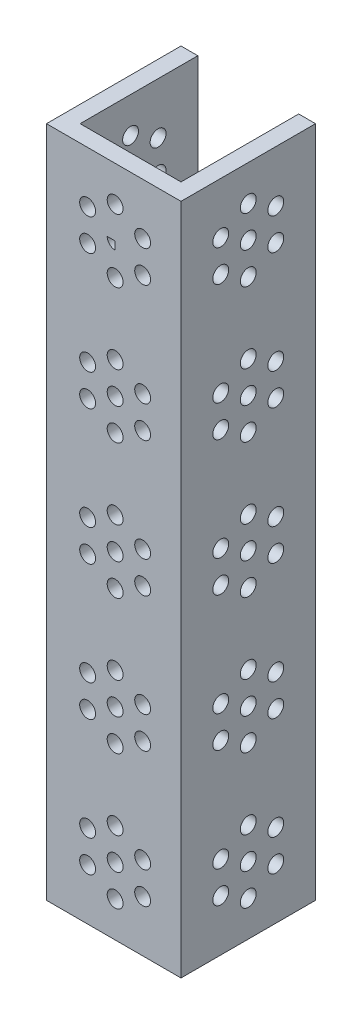
SolidWorks part; units mm, degrees
ref_plane "Front" through (0, 0, 0) normal (0, 0, 1) x (1, 0, 0)
ref_plane "Top" through (0, 0, 0) normal (0, 1, 0) x (1, 0, 0)
ref_plane "Right" through (0, 0, 0) normal (1, 0, 0) x (0, 0, -1)
sketch "Sketch2" plane through (0, 0, 0) normal (0, 1, 0) x (1, 0, 0)
  line L0 (12.7, 25.4) -> (12.7, 3.175)
  line L1 (0, 0) -> (25.4, 0)
  line L2 (0, 0) -> (0, 25.4)
  line L3 (0, 25.4) -> (25.4, 25.4)
  line L4 (25.4, 0) -> (25.4, 25.4)
  line L5 (12.7, 3.175) -> (22.225, 3.175)
  line L6 (12.7, 3.175) -> (3.175, 3.175)
  line L7 (3.175, 3.175) -> (3.175, 25.4)
  line L8 (22.225, 3.175) -> (22.225, 25.4)
  dimension "D1" = 25.4
  dimension "D2" = 25.4
  dimension "D3" = 22.225
  dimension "D4" = 9.525
  dimension "D5" = 9.525
extrude "Boss-Extrude1" add sketch "Sketch2" along normal blind 127 contours L8 L5 L6 L7 L3 L2 L1 L4
sketch "Sketch3" plane through (0, 0, 0) normal (-1, 0, 0) x (0, 0, 1)
  line L0 (-25.4, 0) -> (-25.4, 25.4)
  line L1 (-25.4, 127) -> (-25.4, 0) construction
  circle A0 centre (-12.7, 12.7) radius 1.5
  circle A1 centre (-12.7, 18.7) radius 1.5
  circle A2 centre (-7.5038, 15.7) radius 1.5
  circle A3 centre (-7.5038, 9.7) radius 1.5
  circle A4 centre (-12.7, 6.7) radius 1.5
  circle A5 centre (-17.8962, 9.7) radius 1.5
  circle A6 centre (-17.8962, 15.7) radius 1.5
  circle A7 centre (-12.7, 32.1) radius 1.5
  circle A8 centre (-17.8962, 35.1) radius 1.5
  circle A9 centre (-17.8962, 41.1) radius 1.5
  circle A10 centre (-12.7, 38.1) radius 1.5
  circle A11 centre (-12.7, 44.1) radius 1.5
  circle A12 centre (-7.5038, 41.1) radius 1.5
  circle A13 centre (-7.5038, 35.1) radius 1.5
  circle A14 centre (-12.7, 57.5) radius 1.5
  circle A15 centre (-17.8962, 60.5) radius 1.5
  circle A16 centre (-17.8962, 66.5) radius 1.5
  circle A17 centre (-12.7, 63.5) radius 1.5
  circle A18 centre (-12.7, 69.5) radius 1.5
  circle A19 centre (-7.5038, 66.5) radius 1.5
  circle A20 centre (-7.5038, 60.5) radius 1.5
  circle A21 centre (-12.7, 82.9) radius 1.5
  circle A22 centre (-17.8962, 85.9) radius 1.5
  circle A23 centre (-17.8962, 91.9) radius 1.5
  circle A24 centre (-12.7, 88.9) radius 1.5
  circle A25 centre (-12.7, 94.9) radius 1.5
  circle A26 centre (-7.5038, 91.9) radius 1.5
  circle A27 centre (-7.5038, 85.9) radius 1.5
  circle A28 centre (-12.7, 108.3) radius 1.5
  circle A29 centre (-17.8962, 111.3) radius 1.5
  circle A30 centre (-17.8962, 117.3) radius 1.5
  circle A31 centre (-12.7, 114.3) radius 1.5
  circle A32 centre (-12.7, 120.3) radius 1.5
  circle A33 centre (-7.5038, 117.3) radius 1.5
  circle A34 centre (-7.5038, 111.3) radius 1.5
  point P26 (-12.7, 12.7)
  dimension "D3" = 6
  dimension "D1" = 25.4
  dimension "D2" = 6
  dimension "D4" = 5
extrude "Cut-Extrude1" cut sketch "Sketch3" against normal through all contours A5 | A6 | A1 | A0 | A4 | A3 | A2 | A8 | A9 | A11 | A10 | A13 | A12 | A14 | A17 | A7 | A15 | A16 | A18 | A19 | A20 | A22 | A23 | A21 | A24 | A27 | A26 | A25 | A29 | A28 | A30 | A32 | A31 | A34 | A33
sketch "Sketch4" plane through (0, 0, 0) normal (0, 0, 1) x (1, 0, 0)
  line L0 (0, 127) -> (0, 101.6)
  line L1 (0, 127) -> (0, 0) construction
  line L2 (0, 114.3) -> (25.4, 114.3)
  line L3 (25.4, 127) -> (25.4, 0) construction
  line L4 (12.9637, 114.3) -> (12.9637, 108.3)
  circle A0 centre (12.9637, 114.3) radius 1.5
  circle A1 centre (12.9637, 108.3) radius 1.5
  circle A2 centre (7.7675, 111.3) radius 1.5
  circle A3 centre (7.7675, 117.3) radius 1.5
  circle A4 centre (12.9637, 120.3) radius 1.5
  circle A5 centre (18.1598, 117.3) radius 1.5
  circle A6 centre (18.1598, 111.3) radius 1.5
  circle A7 centre (12.9637, 82.9) radius 1.5
  circle A8 centre (12.9637, 88.9) radius 1.5
  circle A9 centre (12.9637, 94.9) radius 1.5
  circle A10 centre (18.1598, 91.9) radius 1.5
  circle A11 centre (18.1598, 85.9) radius 1.5
  circle A12 centre (7.7675, 91.9) radius 1.5
  circle A13 centre (7.7675, 85.9) radius 1.5
  circle A14 centre (12.9637, 57.5) radius 1.5
  circle A15 centre (12.9637, 63.5) radius 1.5
  circle A16 centre (12.9637, 69.5) radius 1.5
  circle A17 centre (18.1598, 66.5) radius 1.5
  circle A18 centre (18.1598, 60.5) radius 1.5
  circle A19 centre (7.7675, 66.5) radius 1.5
  circle A20 centre (7.7675, 60.5) radius 1.5
  circle A21 centre (12.9637, 32.1) radius 1.5
  circle A22 centre (12.9637, 38.1) radius 1.5
  circle A23 centre (12.9637, 44.1) radius 1.5
  circle A24 centre (18.1598, 41.1) radius 1.5
  circle A25 centre (18.1598, 35.1) radius 1.5
  circle A26 centre (7.7675, 41.1) radius 1.5
  circle A27 centre (7.7675, 35.1) radius 1.5
  circle A28 centre (12.9637, 6.7) radius 1.5
  circle A29 centre (12.9637, 12.7) radius 1.5
  circle A30 centre (12.9637, 18.7) radius 1.5
  circle A31 centre (18.1598, 15.7) radius 1.5
  circle A32 centre (18.1598, 9.7) radius 1.5
  circle A33 centre (7.7675, 15.7) radius 1.5
  circle A34 centre (7.7675, 9.7) radius 1.5
  point P13 (0, 0)
  point P14 (0, 0)
  point P26 (12.9637, 114.3)
  point P82 (0, 0)
  point P83 (0, 0)
  point P84 (0, 0)
  dimension "D2" = 6
  dimension "D3" = 6
  dimension "D1" = 25.4
  dimension "D4" = 5
extrude "Cut-Extrude2" cut sketch "Sketch4" against normal blind 10
